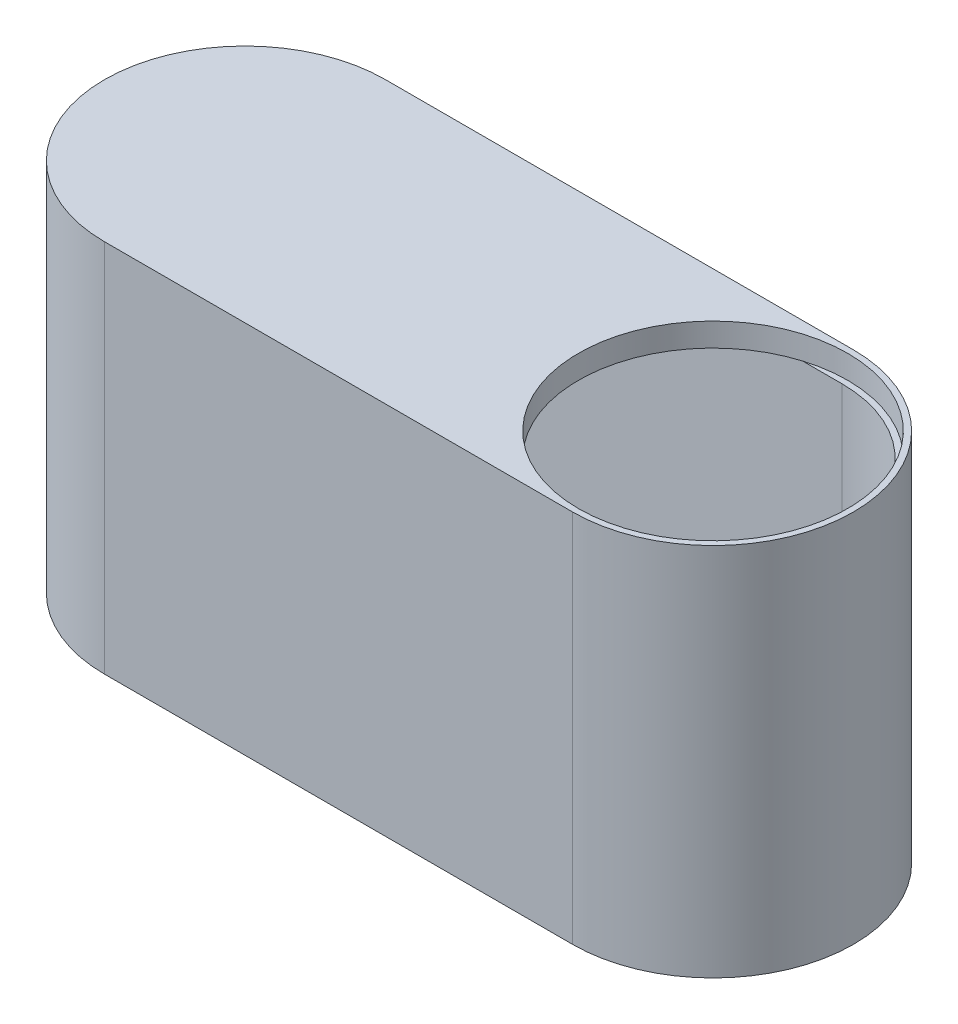
SolidWorks part; units mm, degrees
ref_plane "Front Plane" through (0, 0, 0) normal (0, 0, 1) x (1, 0, 0)
ref_plane "Top Plane" through (0, 0, 0) normal (0, 1, 0) x (1, 0, 0)
ref_plane "Right Plane" through (0, 0, 0) normal (1, 0, 0) x (0, 0, -1)
sketch "Sketch2" plane through (0, 0, 0) normal (0, 1, 0) x (1, 0, 0)
  line L0 (77.2984, 53.6856) -> (117.2984, 53.6856) construction
  line L1 (77.2984, 64.1856) -> (117.2984, 64.1856) construction
  line L2 (77.2984, 43.1856) -> (117.2984, 43.1856) construction
  line L3 (117.2984, 64.1856) -> (77.2984, 64.1856) construction
  line L4 (77.2984, 64.6856) -> (117.2984, 64.6856)
  line L5 (77.2984, 42.6856) -> (117.2984, 42.6856)
  line L6 (77.2984, 41.6856) -> (117.2984, 41.6856)
  line L7 (77.2984, 65.6856) -> (117.2984, 65.6856)
  arc A0 (77.2984, 64.1856) -> (77.2984, 43.1856) centre (77.2984, 53.6856) ccw construction
  arc A1 (117.2984, 43.1856) -> (117.2984, 64.1856) centre (117.2984, 53.6856) ccw construction
  arc A2 (77.2984, 64.1856) -> (77.2984, 43.1856) centre (77.2984, 53.6856) ccw construction
  arc A3 (117.2984, 42.6856) -> (117.2984, 64.6856) centre (117.2984, 53.6856) ccw
  arc A4 (77.2984, 64.6856) -> (77.2984, 42.6856) centre (77.2984, 53.6856) ccw
  arc A5 (77.2984, 65.6856) -> (77.2984, 41.6856) centre (77.2984, 53.6856) ccw
  arc A6 (117.2984, 41.6856) -> (117.2984, 65.6856) centre (117.2984, 53.6856) ccw
  point P2 (97.2984, 53.6856)
  dimension "D1" = 0.5
  dimension "D2" = 1
extrude "Boss-Extrude1" add sketch "Sketch2" along normal blind 30
sketch "Sketch3" plane through (0, 30, 0) normal (0, 1, 0) x (1, 0, 0)
  line L0 (77.2984, 53.6856) -> (117.2984, 53.6856) construction
  line L1 (77.2984, 65.6856) -> (117.2984, 65.6856)
  line L2 (77.2984, 41.6856) -> (117.2984, 41.6856)
  arc A0 (77.2984, 65.6856) -> (77.2984, 41.6856) centre (77.2984, 53.6856) ccw
  arc A1 (117.2984, 41.6856) -> (117.2984, 65.6856) centre (117.2984, 53.6856) ccw
  arc A2 (117.2984, 41.6856) -> (117.2984, 65.6856) centre (117.2984, 53.6856) ccw construction
  circle A3 centre (117.2984, 53.6856) radius 11.5
  point P4 (97.2984, 53.6856)
extrude "Boss-Extrude2" add sketch "Sketch3" along normal blind 2
